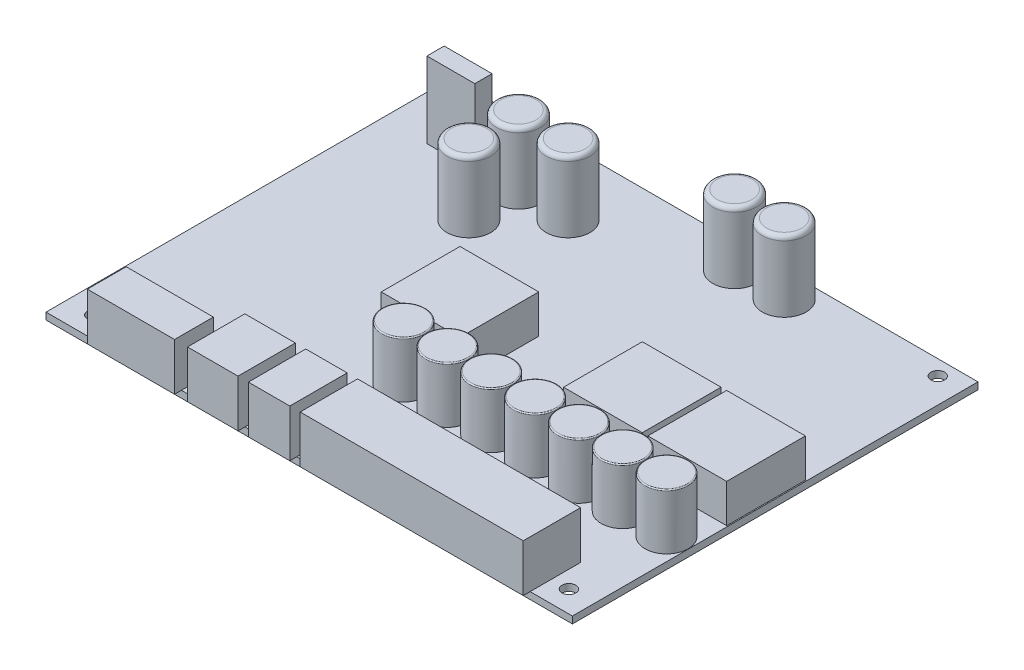
SolidWorks part; units mm, degrees
ref_plane "Front Plane" through (0, 0, 0) normal (0, 0, 1) x (1, 0, 0)
ref_plane "Top Plane" through (0, 0, 0) normal (0, 1, 0) x (1, 0, 0)
ref_plane "Right Plane" through (0, 0, 0) normal (1, 0, 0) x (0, 0, -1)
sketch "Sketch1" plane through (0, 0, 0) normal (0, 1, 0) x (1, 0, 0)
  line L1 (-61, 47) -> (61, 47)
  line L2 (-61, 47) -> (-61, -47)
  line L3 (-61, -47) -> (61, -47)
  line L4 (61, 47) -> (61, -47)
  line L5 (-61, 47) -> (61, -47) construction
  line L6 (-61, -47) -> (61, 47) construction
  point P0 (0, 0)
  dimension "D1" = 122
  dimension "D2" = 94
extrude "Boss-Extrude1" add sketch "Sketch1" along normal blind 1.6
sketch "Sketch2" plane through (0, 1.6, 0) normal (0, 1, 0) x (1, 0, 0)
  line L0 (61, 47) -> (-61, 47) construction
  line L1 (55.18, -42) -> (-54.82, -42) construction
  line L2 (55.18, -42) -> (55.18, 43.5) construction
  line L3 (55.18, 43.5) -> (-54.82, 43.5) construction
  line L4 (-54.82, -42) -> (-54.82, 43.5) construction
  line L7 (61, -47) -> (61, 47) construction
  circle A0 centre (-54.82, 43.5) radius 1.585
  circle A1 centre (55.18, 43.5) radius 1.585
  circle A2 centre (55.18, -42) radius 1.585
  circle A3 centre (-54.82, -42) radius 1.585
  point P0 (0, 0)
  dimension "D1" = 3.17
  dimension "D2" = 3.5
  dimension "D3" = 5.82
  dimension "D4" = 85.5
  dimension "D5" = 110
extrude "Cut-Extrude1" cut sketch "Sketch2" against normal through all
sketch "Sketch3" plane through (0, 1.6, 0) normal (0, 1, 0) x (1, 0, 0)
  line L0 (10.5, 41.0895) -> (22, 41.0895) construction
  line L1 (-19, 20.5) -> (-30.5, 20.5) construction
  line L2 (-19, 20.5) -> (-19, 32) construction
  line L3 (-19, 32) -> (-30.5, 32) construction
  line L4 (-30.5, 20.5) -> (-30.5, 32) construction
  line L5 (-19, 20.5) -> (-30.5, 32) construction
  line L6 (-19, 32) -> (-30.5, 20.5) construction
  line L7 (61, -47) -> (61, 47) construction
  line L8 (61, 47) -> (-61, 47) construction
  circle A0 centre (22, 41.0895) radius 5.085
  circle A1 centre (10.5, 41.0895) radius 5.085
  circle A2 centre (-19, 32) radius 5.085
  circle A3 centre (-30.5, 32) radius 5.085
  circle A4 centre (-30.5, 20.5) radius 5.085
  point P4 (-24.75, 26.25)
  dimension "D1" = 10.17
  dimension "D2" = 11.5
  dimension "D3" = 39
  dimension "D4" = 5.9105
  dimension "D5" = 80
  dimension "D6" = 15
extrude "Boss-Extrude2" add sketch "Sketch3" along normal blind 16.35
fillet "Fillet1" radius 1.016 5 edges at (-30.5, 17.95, -15.415) (-30.5, 17.95, -26.915) (-19, 17.95, -26.915) (10.5, 17.95, -36.0045) (22, 17.95, -36.0045)
sketch "Sketch4" plane through (0, 1.6, 0) normal (0, 1, 0) x (1, 0, 0)
  line L0 (61, -47) -> (61, 47) construction
  line L1 (-61, -47) -> (61, -47) construction
  circle A0 centre (55.92, -20.1) radius 5
  dimension "D1" = 10
  dimension "D2" = 5.08
  dimension "D3" = 26.9
extrude "Boss-Extrude3" add sketch "Sketch4" along normal blind 12.9
fillet "Fillet2" radius 0.254 1 edges at (55.92, 14.5, 25.1)
pattern_linear "LPattern1" count 7 spacing 10.16 along (-1, 0, 0) of "Boss-Extrude3", "Fillet2"
sketch "Sketch5" plane through (0, 1.6, 0) normal (0, 1, 0) x (1, 0, 0)
  line L0 (61, -47) -> (61, 47) construction
  line L1 (60.746, 7.25) -> (42.496, 7.25)
  line L2 (60.746, 7.25) -> (60.746, -11)
  line L3 (60.746, -11) -> (42.496, -11)
  line L4 (42.496, 7.25) -> (42.496, -11)
  line L5 (41.196, -11) -> (22.946, -11)
  line L6 (41.196, -11) -> (41.196, 7.25)
  line L7 (41.196, 7.25) -> (22.946, 7.25)
  line L8 (22.946, -11) -> (22.946, 7.25)
  line L9 (0.946, -13) -> (-17.304, -13)
  line L10 (0.946, -13) -> (0.946, 5.25)
  line L11 (0.946, 5.25) -> (-17.304, 5.25)
  line L12 (-17.304, -13) -> (-17.304, 5.25)
  line L13 (-61, -47) -> (61, -47) construction
  dimension "D1" = 1.3
  dimension "D2" = 0.254
  dimension "D3" = 18.25
  dimension "D4" = 36
  dimension "D5" = 34
  dimension "D6" = 22
extrude "Boss-Extrude4" add sketch "Sketch5" along normal blind 8.9
sketch "Sketch6" plane through (0, 1.6, 0) normal (0, 1, 0) x (1, 0, 0)
  line L1 (-50.6659, 34.9451) -> (-39.5659, 34.9451)
  line L2 (-50.6659, 34.9451) -> (-50.6659, 30.9451)
  line L3 (-50.6659, 30.9451) -> (-39.5659, 30.9451)
  line L4 (-39.5659, 34.9451) -> (-39.5659, 30.9451)
  line L5 (-50.6659, 34.9451) -> (-39.5659, 30.9451) construction
  line L6 (-50.6659, 30.9451) -> (-39.5659, 34.9451) construction
  point P0 (-45.1159, 32.9451)
  dimension "D1" = 11.1
  dimension "D2" = 4
extrude "Boss-Extrude5" add sketch "Sketch6" along normal blind 17.6
sketch "Sketch7" plane through (0, 1.6, 0) normal (0, 1, 0) x (1, 0, 0)
  line L0 (-61, -47) -> (61, -47) construction
  line L1 (-49.81, -39.6) -> (-29.61, -39.6)
  line L2 (-49.81, -39.6) -> (-49.81, -48.6)
  line L3 (-49.81, -48.6) -> (-29.61, -48.6)
  line L4 (-29.61, -39.6) -> (-29.61, -48.6)
  line L5 (-26.61, -35.3) -> (-14.9, -35.3)
  line L6 (-26.61, -35.3) -> (-26.61, -48.6)
  line L7 (-26.61, -48.6) -> (-14.9, -48.6)
  line L8 (-14.9, -35.3) -> (-14.9, -48.6)
  line L9 (-12.5, -35.3) -> (-2.9, -35.3)
  line L10 (-12.5, -35.3) -> (-12.5, -48.6)
  line L11 (-12.5, -48.6) -> (-2.9, -48.6)
  line L12 (-2.9, -35.3) -> (-2.9, -48.6)
  line L13 (-0.5, -35.3) -> (51.2, -35.3)
  line L14 (-0.5, -35.3) -> (-0.5, -48.6)
  line L15 (-0.5, -48.6) -> (51.2, -48.6)
  line L16 (51.2, -35.3) -> (51.2, -48.6)
  line L17 (61, -47) -> (61, 47) construction
  dimension "D1" = 13.3
  dimension "D2" = 1.6
  dimension "D3" = 9
  dimension "D4" = 3
  dimension "D5" = 2.4
  dimension "D6" = 2.4
  dimension "D7" = 9.8
  dimension "D8" = 51.7
  dimension "D9" = 9.6
  dimension "D10" = 11.71
  dimension "D11" = 20.2
extrude "Boss-Extrude6" add sketch "Sketch7" along normal blind 11
